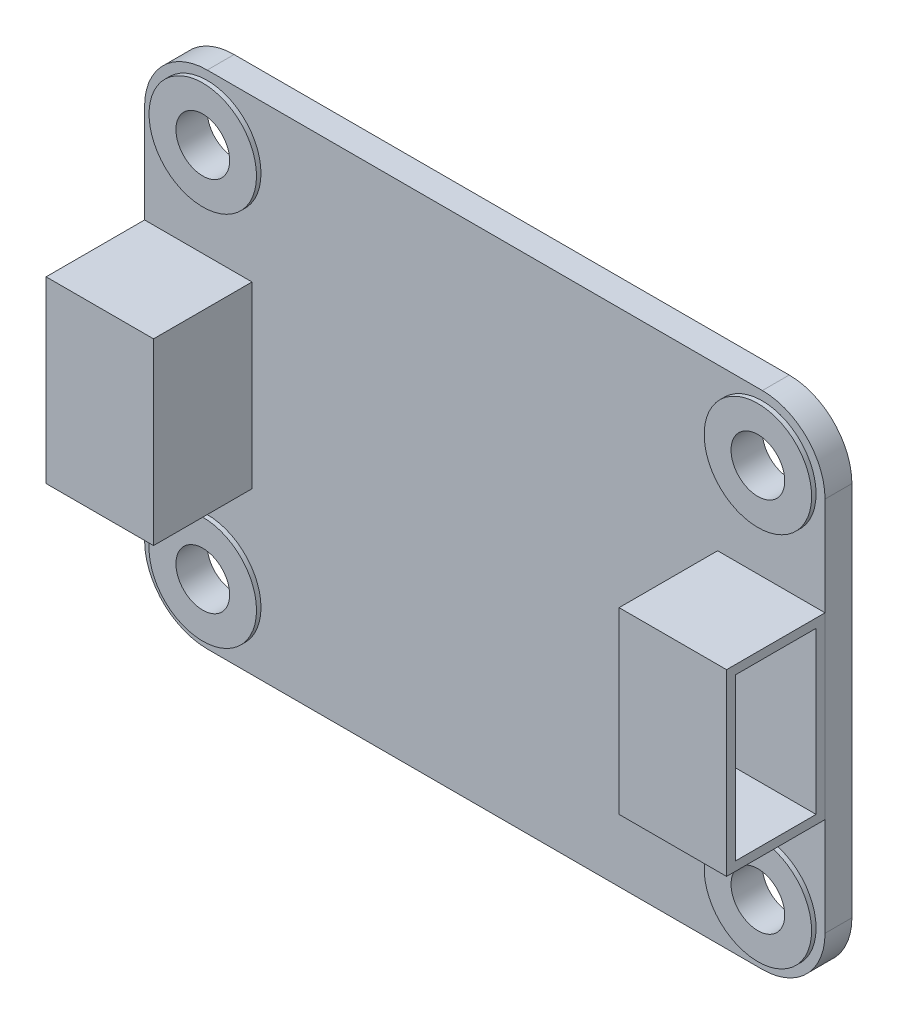
SolidWorks part; units mm, degrees
ref_plane "Plan de face" through (0, 0, 0) normal (0, 0, 1) x (1, 0, 0)
ref_plane "Plan de dessus" through (0, 0, 0) normal (0, 1, 0) x (1, 0, 0)
ref_plane "Plan de droite" through (0, 0, 0) normal (1, 0, 0) x (0, 0, -1)
sketch "Esquisse1" plane through (0, 0, 0) normal (0, 0, 1) x (1, 0, 0)
  line L1 (-15.5, -14) -> (15.5, -14)
  line L2 (-19, -10.5) -> (-19, 10.5)
  line L3 (-15.5, 14) -> (15.5, 14)
  line L4 (19, -10.5) -> (19, 10.5)
  line L5 (-19, -14) -> (19, 14) construction
  line L6 (-19, 14) -> (19, -14) construction
  arc A0 (15.5, 14) -> (19, 10.5) centre (15.5, 10.5) cw
  arc A1 (15.5, -14) -> (19, -10.5) centre (15.5, -10.5) ccw
  arc A2 (-15.5, -14) -> (-19, -10.5) centre (-15.5, -10.5) cw
  arc A3 (-19, 10.5) -> (-15.5, 14) centre (-15.5, 10.5) cw
  circle A4 centre (-15.5, 10.5) radius 1.5
  circle A5 centre (-15.5, -10.5) radius 1.5
  circle A6 centre (15.5, 10.5) radius 1.5
  circle A7 centre (15.5, -10.5) radius 1.5
  point P0 (0, 0)
  dimension "D3" = 3.5
  dimension "D4" = 3
  dimension "D1" = 38
  dimension "D2" = 28
extrude "Boss.-Extru.1" add sketch "Esquisse1" along normal blind 1.5 contours A3 L2 A2 L1 A1 L4 A0 L3 A7 A6 A5 A4
sketch "Esquisse2" plane through (0, 0, 1.5) normal (0, 0, 1) x (1, 0, 0)
  circle A0 centre (15.5, 10.5) radius 3
  circle A1 centre (-15.5, 10.5) radius 3
  circle A2 centre (-15.5, -10.5) radius 3
  circle A3 centre (15.5, -10.5) radius 3
  circle A4 centre (-15.5, -10.5) radius 1.5 construction
  circle A5 centre (15.5, -10.5) radius 1.5 construction
  circle A6 centre (15.5, 10.5) radius 1.5 construction
  circle A7 centre (-15.5, 10.5) radius 1.5 construction
  circle A8 centre (-15.5, -10.5) radius 1.5
  circle A9 centre (15.5, -10.5) radius 1.5
  circle A10 centre (15.5, 10.5) radius 1.5
  circle A11 centre (-15.5, 10.5) radius 1.5
  dimension "D1" = 6
extrude "Boss.-Extru.2" add sketch "Esquisse2" along normal blind 0.25
sketch "Esquisse11" plane through (0, 0, 1.5) normal (0, 0, 1) x (1, 0, 0)
  line L0 (19, -10.5) -> (19, 10.5) construction
  line L1 (19, 5) -> (13, 5)
  line L2 (19, 5) -> (19, -5)
  line L3 (19, -5) -> (13, -5)
  line L4 (13, 5) -> (13, -5)
  point P6 (13, 0)
  dimension "D1" = 10
  dimension "D2" = 6
extrude "Boss.-Extru.9" add sketch "Esquisse11" along normal blind 5.5 separate body
shell "Coque1" thickness 0.5
mirror "Symétrie1" about plane through (0, 0, 0) normal (1, 0, 0) of bodies 112
